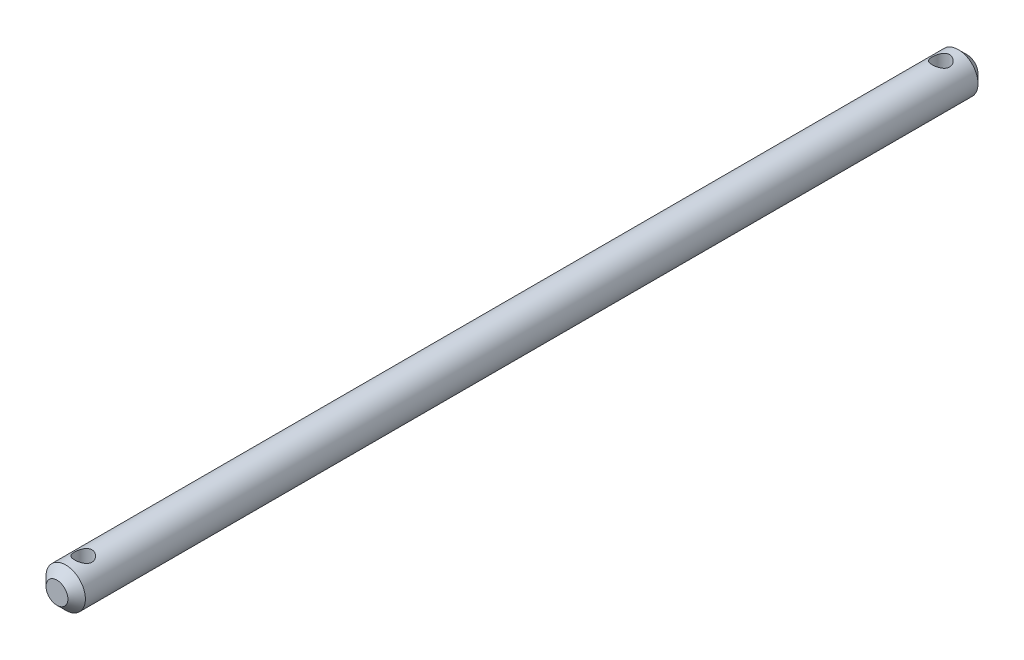
SolidWorks part; units mm, degrees
ref_plane "前基準面" through (0, 0, 0) normal (0, 0, 1) x (1, 0, 0)
ref_plane "上基準面" through (0, 0, 0) normal (0, 1, 0) x (1, 0, 0)
ref_plane "右基準面" through (0, 0, 0) normal (1, 0, 0) x (0, 0, -1)
sketch "草圖1" plane through (0, 0, 0) normal (0, 0, 1) x (1, 0, 0)
  circle A0 centre (0, 0) radius 2.25
  dimension "D1" = 4.5
extrude "填料-伸長1" add sketch "草圖1" along normal blind 104
chamfer "導角1" distance 1 angle 45 2 edges at (2.25, 0, 0) (2.25, 0, 104)
sketch "草圖2" plane through (0, 0, 0) normal (0, 1, 0) x (1, 0, 0)
  line L0 (0, 0) -> (0, -3) construction
  line L1 (2.25, -52) -> (14.0594, -52) construction
  line L2 (2.25, -103) -> (2.25, -1) construction
  circle A0 centre (0, -3) radius 1
  circle A1 centre (0, -101) radius 1
  dimension "D1" = 2
  dimension "D2" = 3
extrude "除料-伸長1" cut sketch "草圖2" against normal through all both and the other way through all
